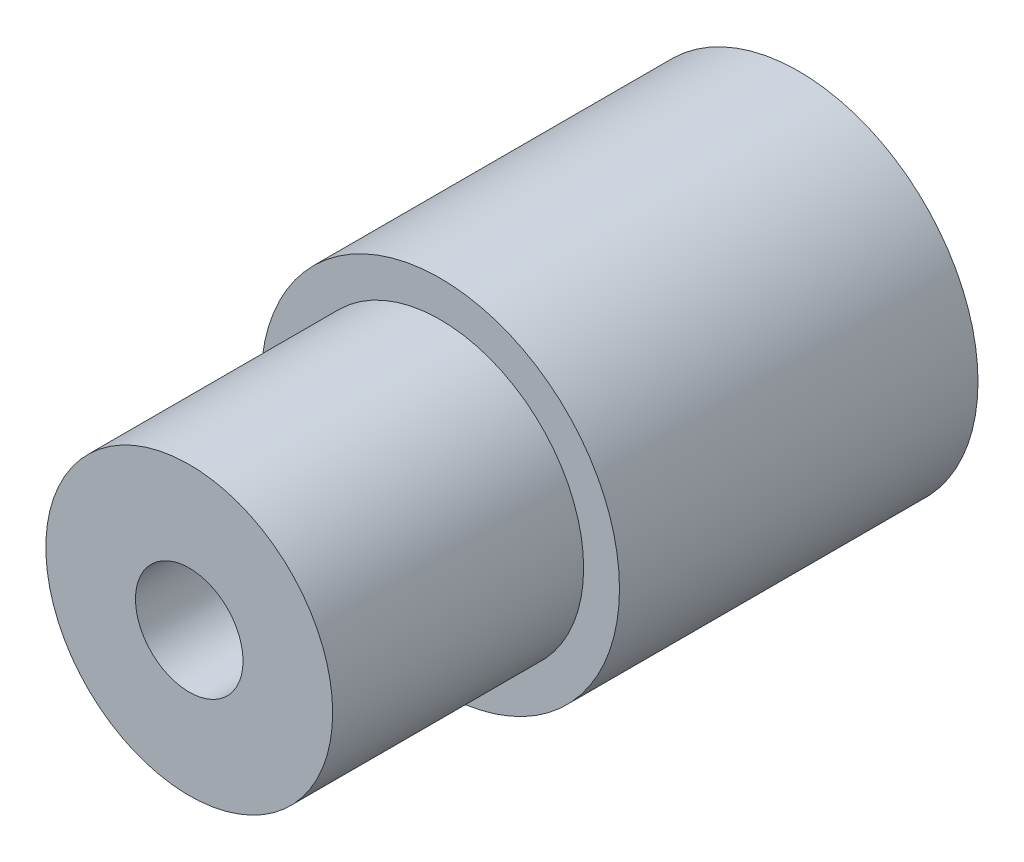
SolidWorks part; units mm, degrees
ref_plane "Front Plane" through (0, 0, 0) normal (0, 0, 1) x (1, 0, 0)
ref_plane "Top Plane" through (0, 0, 0) normal (0, 1, 0) x (1, 0, 0)
ref_plane "Right Plane" through (0, 0, 0) normal (1, 0, 0) x (0, 0, -1)
sketch "Sketch1" plane through (0, 0, 0) normal (0, 0, 1) x (1, 0, 0)
  circle A0 centre (0, 0) radius 5
  circle A1 centre (0, 0) radius 1.5
  dimension "D1" = 10
  dimension "D2" = 3
extrude "Boss-Extrude1" add sketch "Sketch1" along normal blind 10
sketch "Sketch2" plane through (0, 0, 10) normal (0, 0, 1) x (1, 0, 0)
  circle A0 centre (0, 0) radius 4
  circle A1 centre (0, 0) radius 1.5 construction
  circle A2 centre (0, 0) radius 1.5
  dimension "D1" = 8
extrude "Boss-Extrude2" add sketch "Sketch2" along normal blind 7
